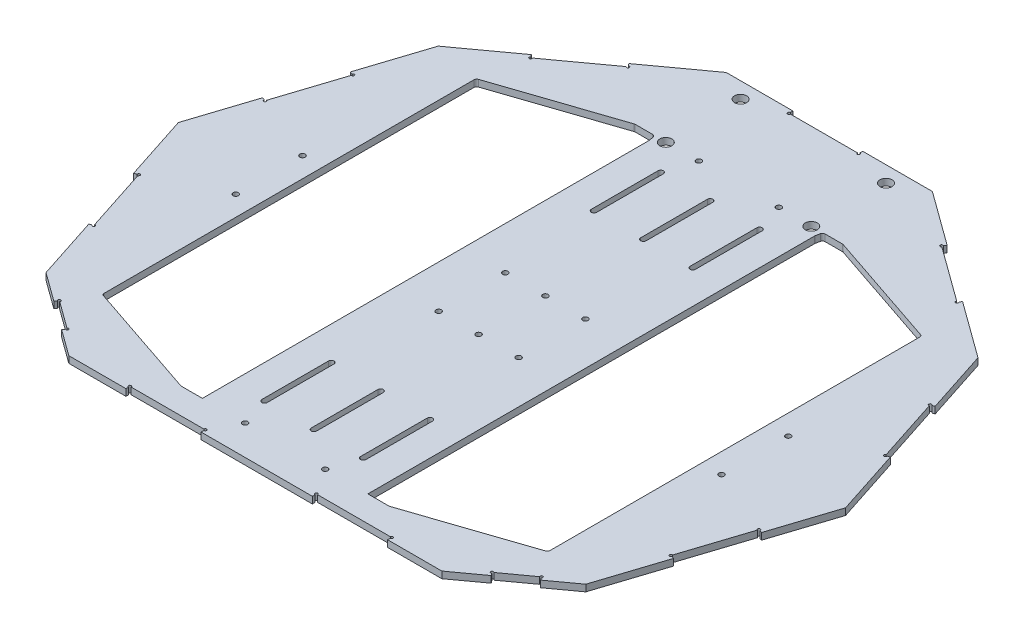
SolidWorks part; units mm, degrees
material "Alumina"
ref_plane "Front Plane" through (0, 0, 0) normal (0, 0, 1) x (1, 0, 0)
ref_plane "Top Plane" through (0, 0, 0) normal (0, 1, 0) x (1, 0, 0)
ref_plane "Right Plane" through (0, 0, 0) normal (1, 0, 0) x (0, 0, -1)
sketch "Sketch1" plane through (0, 0, 0) normal (0, 1, 0) x (1, 0, 0)
  circle A0 centre (0, 0) radius 250
extrude "Boss-Extrude1" add sketch "Sketch1" along normal blind 5
sketch "Sketch2" plane through (0, 5, 0) normal (0, 1, 0) x (1, 0, 0)
  line L0 (73, -140) -> (167, -140)
  line L1 (-167, -140) -> (-73, -140)
  line L2 (-167, -140) -> (-167, 140)
  line L3 (-167, 140) -> (-73, 140)
  line L4 (-73, -140) -> (-73, 140)
  line L5 (-167, -140) -> (-73, 140) construction
  line L6 (-167, 140) -> (-73, -140) construction
  line L7 (73, 140) -> (167, -140) construction
  line L8 (73, -140) -> (73, 140)
  line L9 (73, 140) -> (167, 140)
  line L10 (73, -140) -> (167, 140) construction
  line L11 (167, -140) -> (167, 140)
  point P0 (-120, 0)
  point P5 (120, 0)
  dimension "D1" = 280
  dimension "D2" = 94
  dimension "D3" = 280
  dimension "D4" = 94
  dimension "D5" = 120
  dimension "D6" = 120
extrude "Cut-Extrude1" cut sketch "Sketch2" against normal through all
sketch "Sketch3" plane through (0, 5, 0) normal (0, 1, 0) x (1, 0, 0)
  line L4 (-167, 140) -> (-167, -140) construction
  line L5 (167, -140) -> (167, 140) construction
  circle A0 centre (0, 25) radius 2
  circle A1 centre (0, -25) radius 2
  circle A2 centre (-182, -25) radius 2
  circle A3 centre (-182, 25) radius 2
  circle A4 centre (182, -25) radius 2
  circle A5 centre (182, 25) radius 2
  dimension "D1" = 25
  dimension "D2" = 15
  dimension "D3" = 15
  dimension "D4" = 15
  dimension "D5" = 15
extrude "Cut-Extrude2" cut sketch "Sketch3" against normal through all
sketch "Sketch4" plane through (0, 5, 0) normal (0, 1, 0) x (1, 0, 0)
  line L0 (-73, -140) -> (-73, 140) construction
  line L1 (-83, -67.5) -> (-63, -67.5)
  line L2 (-83, -67.5) -> (-83, 67.5)
  line L3 (-83, 67.5) -> (-63, 67.5)
  line L4 (-63, -67.5) -> (-63, 67.5)
  line L5 (-83, -67.5) -> (-63, 67.5) construction
  line L6 (-83, 67.5) -> (-63, -67.5) construction
  line L7 (63, -67.5) -> (63, -107.5)
  line L8 (-73, 140) -> (-167, 140) construction
  line L9 (-83, 67.5) -> (-83, 107.5)
  line L10 (-83, 107.5) -> (-63, 107.5)
  line L11 (-63, 67.5) -> (-63, 107.5)
  line L12 (83, -67.5) -> (63, -67.5)
  line L13 (83, -67.5) -> (63, 67.5) construction
  line L14 (83, -107.5) -> (63, -107.5)
  line L15 (83, 67.5) -> (63, -67.5) construction
  line L16 (83, 67.5) -> (83, -67.5)
  line L17 (83, 67.5) -> (63, 67.5)
  line L18 (-83, 140) -> (-63, 140)
  line L19 (83, -67.5) -> (83, -107.5)
  line L20 (63, 67.5) -> (63, -67.5)
  line L21 (-83, 140) -> (-83, 67.5)
  line L22 (-83, 67.5) -> (-63, 67.5)
  line L23 (-63, 140) -> (-63, 67.5)
  line L24 (73, -140) -> (167, -140) construction
  line L25 (83, -140) -> (63, -140)
  line L26 (83, -140) -> (83, -67.5)
  line L27 (83, -67.5) -> (63, -67.5)
  line L28 (63, -140) -> (63, -67.5)
  line L29 (167, 140) -> (73, 140) construction
  line L30 (83, 140) -> (63, 140)
  line L31 (83, 140) -> (83, 67.5)
  line L32 (83, 67.5) -> (63, 67.5)
  line L33 (63, 140) -> (63, 67.5)
  line L35 (-83, -67.5) -> (-63, -67.5)
  line L36 (-83, -67.5) -> (-83, -140)
  line L37 (-83, -140) -> (-63, -140)
  line L38 (-63, -67.5) -> (-63, -140)
  point P0 (-73, 0)
  point P9 (73, 0)
  line M11 (73, -140) -> (73, 140)
  line M13 (-73, 140) -> (-73, -140)
  dimension "D1" = 135
  dimension "D2" = 20
  dimension "D3" = 40
extrude "Cut-Extrude3" cut sketch "Sketch4" against normal through all contours L17 L20 L12 M11 | L1 L4 L3 M13 | L3 L11 L10 M13 | L14 L12 L7 M11 | L23 L18 L10 M13 | L28 L25 L14 M11 | L38 L1 L37 M13 | L30 L33 L17 M11
sketch "Sketch5" plane through (0, 5, 0) normal (0, 1, 0) x (1, 0, 0)
  line L0 (-139.7542, -192.3552) -> (139.7542, -192.3552)
  line L1 (202.2542, 146.9463) -> (77.2542, 237.7641)
  line L2 (77.2542, 237.7641) -> (-77.2542, 237.7641)
  line L3 (-77.2542, 237.7641) -> (-202.2542, 146.9463)
  line L4 (-202.2542, 146.9463) -> (-250, 0)
  line L5 (-250, 0) -> (-202.2542, -146.9463)
  line L7 (-202.2542, -146.9463) -> (-139.7542, -192.3552)
  line L9 (202.2542, -146.9463) -> (250, 0)
  line L10 (250, 0) -> (202.2542, 146.9463)
  line L11 (139.7542, -192.3552) -> (202.2542, -146.9463)
  line L14 (-77.2542, -237.7641) -> (77.2542, -237.7641) [skipped]
  line L15 (-202.2542, -146.9463) -> (-77.2542, -237.7641) [skipped]
  line L16 (77.2542, -237.7641) -> (202.2542, -146.9463) [skipped]
  circle A0 centre (0, 0) radius 237.7641 construction
extrude "Cut-Extrude4" cut sketch "Sketch5" against normal blind 6 flip side to cut
sketch "Sketch6" plane through (0, 5, 0) normal (0, 1, 0) x (1, 0, 0)
  line L0 (35, -124.458) -> (35, -142.458)
  line L1 (39, -124.458) -> (39, -142.458)
  line L2 (2, -124.458) -> (2, -142.458)
  line L3 (-2, -104.458) -> (-2, -142.458)
  line L4 (-2, -104.458) -> (-2, -98.458)
  line L5 (-2, -142.458) -> (-2, -148.458)
  line L6 (2, -124.458) -> (2, -98.458)
  line L7 (2, -142.458) -> (2, -148.458)
  line L8 (35, -124.458) -> (35, -98.458)
  line L9 (39, -124.458) -> (39, -98.458)
  line L10 (35, -142.458) -> (35, -148.458)
  line L11 (39, -142.458) -> (39, -148.458)
  line L12 (-39, 148.458) -> (-39, 98.458)
  line L13 (-35, 148.458) -> (-35, 98.458)
  line L14 (2, 122.458) -> (2, 104.458)
  line L15 (-2, 122.458) -> (-2, 104.458)
  line L16 (-2, 104.458) -> (-2, 98.458)
  line L17 (2, 122.458) -> (2, 148.458)
  line L18 (-2, 122.458) -> (-2, 148.458)
  line L19 (2, 104.458) -> (2, 98.458)
  line L20 (35, 122.458) -> (35, 148.458)
  line L21 (39, 104.458) -> (39, 98.458)
  line L22 (39, 122.458) -> (39, 104.458)
  line L23 (39, 122.458) -> (39, 148.458)
  line L24 (35, 122.458) -> (35, 104.458)
  line L25 (35, 104.458) -> (35, 98.458)
  line L26 (-35, -124.458) -> (-35, -98.458)
  line L27 (-35, -124.458) -> (-35, -142.458)
  line L28 (-39, -142.458) -> (-39, -148.458)
  line L29 (-35, -142.458) -> (-35, -148.458)
  line L30 (-39, -104.458) -> (-39, -142.458)
  line L31 (-39, -104.458) -> (-39, -98.458)
  arc A0 (-39, 148.458) -> (-35, 148.458) centre (-37, 148.458) cw
  arc A1 (-2, 148.458) -> (2, 148.458) centre (0, 148.458) cw
  arc A2 (2, 98.458) -> (-2, 98.458) centre (0, 98.458) cw
  arc A3 (-39, 98.458) -> (-35, 98.458) centre (-37, 98.458) ccw
  arc A4 (2, -98.458) -> (-2, -98.458) centre (0, -98.458) ccw
  arc A5 (-2, -148.458) -> (2, -148.458) centre (0, -148.458) ccw
  arc A6 (35, -98.458) -> (39, -98.458) centre (37, -98.458) cw
  arc A7 (39, -148.458) -> (35, -148.458) centre (37, -148.458) cw
  arc A8 (39, 98.458) -> (35, 98.458) centre (37, 98.458) cw
  arc A9 (35, 148.458) -> (39, 148.458) centre (37, 148.458) cw
  arc A10 (-35, -98.458) -> (-39, -98.458) centre (-37, -98.458) ccw
  arc A11 (-39, -148.458) -> (-35, -148.458) centre (-37, -148.458) ccw
  dimension "D4" = 50
  dimension "D7" = 50
  dimension "D1" = 6
  dimension "D2" = 6
  dimension "D3" = 6
  dimension "D5" = 50
  dimension "D6" = 50
  dimension "D8" = 50
  dimension "D9" = 6
  dimension "D10" = 6
  dimension "D11" = 50
extrude "Cut-Extrude5" cut sketch "Sketch6" against normal through all
sketch "Sketch7" plane through (0, 5, 0) normal (0, 1, 0) x (1, 0, 0)
  line L0 (-233.8693, -49.6452) -> (-217.7077, -99.3854)
  line L1 (-233.8693, -49.6452) -> (-231.0161, -48.7181)
  line L2 (-217.7077, -99.3854) -> (-214.8546, -98.4584)
  line L3 (-231.0161, -48.7181) -> (-214.8546, -98.4584)
  line L4 (-250, 0) -> (-202.2542, -146.9463) construction
  line L5 (-218.3849, 97.3012) -> (-234.5465, 47.5609)
  line L6 (-218.3849, 97.3012) -> (-215.5318, 96.3741)
  line L7 (-234.5465, 47.5609) -> (-231.6934, 46.6339)
  line L8 (-215.5318, 96.3741) -> (-231.6934, 46.6339)
  line L9 (-119.4849, 207.0817) -> (-161.7965, 176.3406)
  line L10 (-119.4849, 207.0817) -> (-117.7216, 204.6547)
  line L11 (-161.7965, 176.3406) -> (-160.0332, 173.9135)
  line L12 (-117.7216, 204.6547) -> (-160.0332, 173.9135)
  line L13 (25.0542, 237.7641) -> (-27.2458, 237.7641)
  line L14 (25.0542, 237.7641) -> (25.0542, 234.7641)
  line L15 (-27.2458, 237.7641) -> (-27.2458, 234.7641)
  line L16 (25.0542, 234.7641) -> (-27.2458, 234.7641)
  line L17 (160.0236, 177.6287) -> (117.712, 208.3699)
  line L18 (160.0236, 177.6287) -> (158.2602, 175.2017)
  line L19 (117.712, 208.3699) -> (115.9486, 205.9428)
  line L20 (158.2602, 175.2017) -> (115.9486, 205.9428)
  line L21 (233.8693, 49.6452) -> (217.7077, 99.3854)
  line L22 (233.8693, 49.6452) -> (231.0161, 48.7181)
  line L23 (217.7077, 99.3854) -> (214.8546, 98.4584)
  line L24 (231.0161, 48.7181) -> (214.8546, 98.4584)
  line L25 (218.3849, -97.3012) -> (234.5465, -47.5609)
  line L26 (218.3849, -97.3012) -> (215.5318, -96.3741)
  line L27 (234.5465, -47.5609) -> (231.6934, -46.6339)
  line L28 (215.5318, -96.3741) -> (231.6934, -46.6339)
  line L29 (-180.8315, -162.5109) -> (-159.3925, -178.0872)
  line L30 (-180.8315, -162.5109) -> (-179.0681, -160.0838)
  line L31 (-159.3925, -178.0872) -> (-157.6292, -175.6601)
  line L32 (-179.0681, -160.0838) -> (-157.6292, -175.6601)
  line L33 (-202.2542, -146.9463) -> (-139.7542, -192.3552) construction
  line L34 (161.177, -176.7907) -> (182.616, -161.2144)
  line L35 (161.177, -176.7907) -> (159.4137, -174.3636)
  line L36 (182.616, -161.2144) -> (180.8526, -158.7873)
  line L37 (159.4137, -174.3636) -> (180.8526, -158.7873)
  line L38 (139.7542, -192.3552) -> (202.2542, -146.9463) construction
  line L39 (-139.7542, -192.3552) -> (139.7542, -192.3552) construction
  line L40 (-96.9742, -192.3552) -> (-40.5742, -192.3552)
  line L41 (119.4849, -207.0817) -> (161.7965, -176.3406) [skipped]
  line L42 (119.4849, -207.0817) -> (117.7216, -204.6547) [skipped]
  line L43 (161.7965, -176.3406) -> (160.0332, -173.9135) [skipped]
  line L44 (117.7216, -204.6547) -> (160.0332, -173.9135) [skipped]
  line L45 (-25.0542, -237.7641) -> (27.2458, -237.7641) [skipped]
  line L46 (-25.0542, -237.7641) -> (-25.0542, -234.7641) [skipped]
  line L47 (27.2458, -237.7641) -> (27.2458, -234.7641) [skipped]
  line L48 (-25.0542, -234.7641) -> (27.2458, -234.7641) [skipped]
  line L49 (-160.0236, -177.6287) -> (-117.712, -208.3699) [skipped]
  line L50 (-160.0236, -177.6287) -> (-158.2602, -175.2017) [skipped]
  line L51 (-117.712, -208.3699) -> (-115.9486, -205.9428) [skipped]
  line L52 (-158.2602, -175.2017) -> (-115.9486, -205.9428) [skipped]
  line L53 (-96.9742, -192.3552) -> (-96.9742, -189.3552)
  line L54 (-96.9742, -189.3552) -> (-40.5742, -189.3552)
  line L55 (-40.5742, -192.3552) -> (-40.5742, -189.3552)
  line L57 (99.1758, -192.3552) -> (42.7758, -192.3552)
  line L58 (99.1758, -192.3552) -> (99.1758, -189.3552)
  line L59 (99.1758, -189.3552) -> (42.7758, -189.3552)
  line L60 (42.7758, -192.3552) -> (42.7758, -189.3552)
  point P45 (0, 0)
  dimension "D1" = 52.2
  dimension "D2" = 10
  dimension "D3" = 26.48
  dimension "D4" = 26.48
  dimension "D5" = 42.78
  dimension "D6" = 83.35
extrude "Cut-Extrude6" cut sketch "Sketch7" against normal through all
sketch "Sketch8" plane through (0, 5, 0) normal (0, 1, 0) x (1, 0, 0)
  circle A0 centre (-27.2458, 234.7641) radius 1
  circle A1 centre (25.0542, 234.7641) radius 1
  circle A2 centre (115.9486, 205.9428) radius 1
  circle A3 centre (158.2602, 175.2017) radius 1
  circle A4 centre (214.8546, 98.4584) radius 1
  circle A5 centre (231.0161, 48.7181) radius 1
  circle A6 centre (231.6934, -46.6339) radius 1
  circle A7 centre (215.5318, -96.3741) radius 1
  circle A8 centre (-179.0681, -160.0838) radius 1
  circle A9 centre (-157.6292, -175.6601) radius 1
  circle A10 centre (-96.9742, -189.3552) radius 1
  circle A11 centre (-40.5742, -189.3552) radius 1
  circle A12 centre (42.7758, -189.3552) radius 1
  circle A13 centre (99.1758, -189.3552) radius 1
  circle A14 centre (-214.8546, -98.4584) radius 1
  circle A15 centre (-231.0161, -48.7181) radius 1
  circle A16 centre (-231.6934, 46.6339) radius 1
  circle A17 centre (-215.5318, 96.3741) radius 1
  circle A18 centre (-160.0332, 173.9135) radius 1
  circle A19 centre (-117.7216, 204.6547) radius 1
  circle A20 centre (160.0332, -173.9135) radius 1 [skipped]
  circle A21 centre (117.7216, -204.6547) radius 1 [skipped]
  circle A22 centre (27.2458, -234.7641) radius 1 [skipped]
  circle A23 centre (-25.0542, -234.7641) radius 1 [skipped]
  circle A24 centre (-115.9486, -205.9428) radius 1 [skipped]
  circle A25 centre (-158.2602, -175.2017) radius 1 [skipped]
  circle A26 centre (180.8526, -158.7873) radius 1
  circle A27 centre (159.4137, -174.3636) radius 1
  point P45 (0, 0)
  dimension "D1" = 10
extrude "Cut-Extrude7" cut sketch "Sketch8" against normal through all
sketch "Sketch9" plane through (0, 5, 0) normal (0, 1, 0) x (1, 0, 0)
  line L2 (-63, 140) -> (-78, 140)
  line L3 (-63, 140) -> (-63, 170)
  line L4 (-63, 170) -> (-78, 170)
  line L5 (-78, 140) -> (-78, 170)
  line L6 (63, -140) -> (78, -140)
  line L7 (63, -140) -> (63, -170)
  line L8 (63, -170) -> (78, -170)
  line L9 (78, -140) -> (78, -170)
extrude "Cut-Extrude8" cut sketch "Sketch9" against normal through all
sketch "Sketch12" plane through (0, 5, 0) normal (0, 1, 0) x (1, 0, 0)
  line L1 (-63, -140) -> (-73, -140)
  line L2 (-63, -140) -> (-63, -160)
  line L3 (-63, -160) -> (-73, -160)
  line L4 (-73, -140) -> (-73, -160)
  line L5 (63, 140) -> (73, 140)
  line L6 (63, 140) -> (63, 160)
  line L7 (63, 160) -> (73, 160)
  line L8 (73, 140) -> (73, 160)
extrude "Cut-Extrude9" cut sketch "Sketch12" against normal through all
sketch "Sketch14" plane through (0, 5, 0) normal (0, 1, 0) x (1, 0, 0)
  circle A0 centre (-30, 170) radius 2
  circle A1 centre (30, 170) radius 2
  circle A3 centre (-30, -170) radius 2
  circle A4 centre (30, -170) radius 2
  circle A5 centre (-30, 25) radius 2
  circle A6 centre (30, 25) radius 2
  circle A7 centre (-30, -25) radius 2
  circle A8 centre (30, -25) radius 2
extrude "Cut-Extrude11" cut sketch "Sketch14" against normal through all
sketch "Sketch16" plane through (0, 5, 0) normal (0, 1, 0) x (1, 0, 0)
  line L0 (-167, 140) -> (-78, 170)
  line L1 (-78, 170) -> (-78, 140)
  line L2 (-78, 140) -> (-167, 140)
  line L3 (73, 160) -> (167, 140)
  line L4 (167, 140) -> (73, 140)
  line L5 (73, 140) -> (73, 160)
  line L6 (78, -170) -> (167, -140)
  line L7 (167, -140) -> (78, -140)
  line L8 (78, -140) -> (78, -170)
  line L9 (78, -170) -> (78.9833, -170.9408)
  line L10 (-167, -140) -> (-73, -160)
  line L11 (-73, -160) -> (-73, -140)
  line L12 (-73, -140) -> (-167, -140)
  line L13 (63, 160) -> (63, 170)
  line L14 (63, 170) -> (78, 170)
  line L15 (78, 170) -> (167, 140)
  line L16 (73, 160) -> (63, 160)
  line L17 (-63, -160) -> (-63, -170)
  line L18 (-63, -170) -> (-78, -170)
  line L19 (-73, -160) -> (-63, -160)
  line L20 (-78, -170) -> (-167, -140)
  line L21 (-167, -140) -> (-166.6341, -140.6763)
extrude "Cut-Extrude13" cut sketch "Sketch16" against normal through all contours L11 L12 L10 | L7 L8 L6 | L5 L4 L3 | L2 L1 L0 | L20 L18 L17 L19 L10 | L16 L3 L15 L14 L13
fillet "Fillet1" radius 2 8 edges at (167, 2.5, 140) (78, 2.5, 170) (-167, 2.5, -140) (-78, 2.5, -170) (-78, 2.5, 170) (-167, 2.5, 140) (78, 2.5, -170) (167, 2.5, -140)
sketch "Sketch17" plane through (0, 0, 0) normal (0, -1, 0) x (1, 0, 0)
  circle A0 centre (-54.4992, -169.7641) radius 4.5
  circle A1 centre (54.5008, -225.7641) radius 4.5
  circle A2 centre (-54.4992, -225.7641) radius 4.5
  circle A3 centre (54.5008, -169.7641) radius 4.5
extrude "Cut-Extrude14" cut sketch "Sketch17" against normal through all
sketch "Sketch18" plane through (0, 5, 0) normal (0, 1, 0) x (1, 0, 0)
  line L0 (-62, 165) -> (-62, -170)
  line L1 (63, 170) -> (62, 165)
  line L2 (-62, -170) -> (-63, -170)
  line L3 (62, 165) -> (62, -170)
  line L4 (63, 170) -> (63, -170)
  line L5 (62, -170) -> (63, -170)
  line L6 (-63, 170) -> (-62, 165)
  line L7 (-63, -170) -> (-63, 170)
extrude "Cut-Extrude15" cut sketch "Sketch18" against normal through all
fillet "Fillet2" radius 2 4 edges at (-62, 2.5, -165) (-63, 2.5, -170) (63, 2.5, -170) (62, 2.5, -165)
